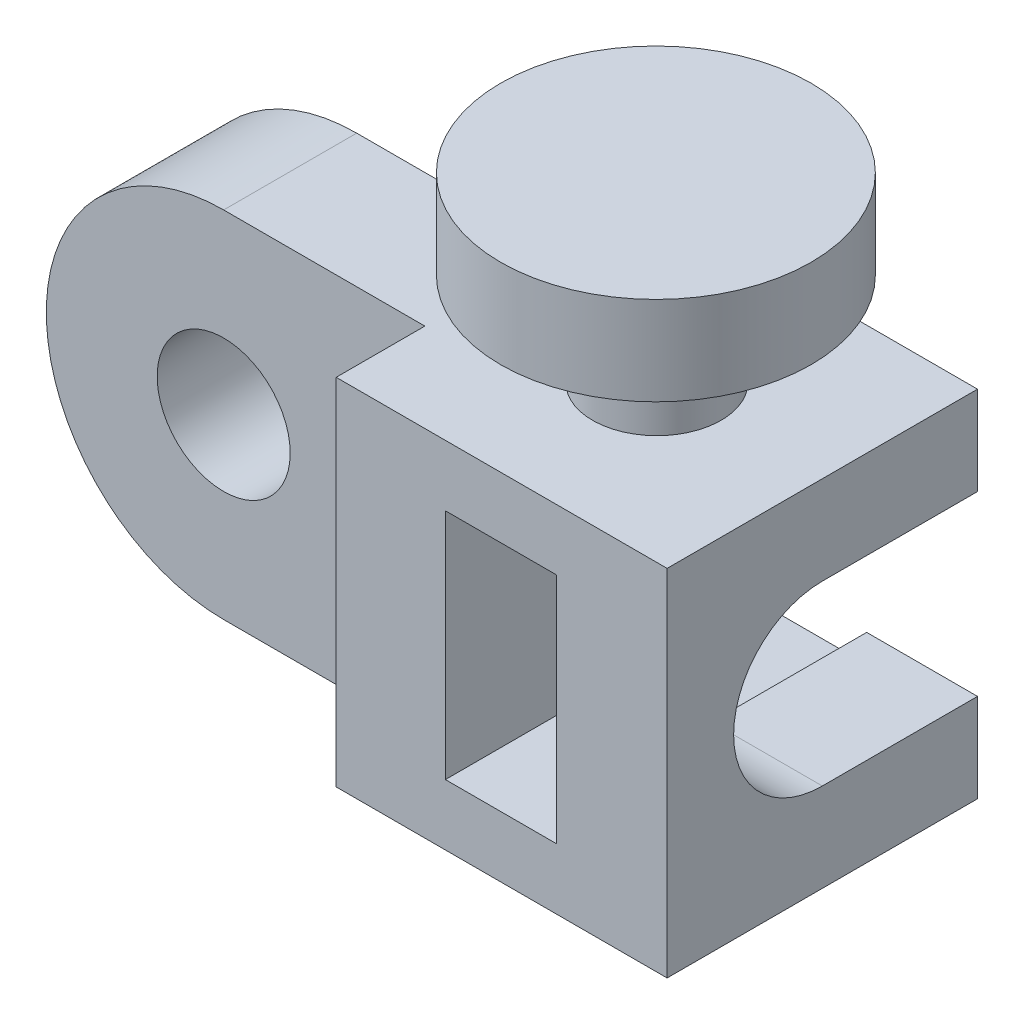
SolidWorks part; units mm, degrees
ref_plane "Спереди" through (0, 0, 0) normal (0, 0, 1) x (1, 0, 0)
ref_plane "Сверху" through (0, 0, 0) normal (0, 1, 0) x (1, 0, 0)
ref_plane "Справа" through (0, 0, 0) normal (1, 0, 0) x (0, 0, -1)
sketch "Sketch1" plane through (0, 0, 0) normal (0, 0, 1) x (1, 0, 0)
  line L0 (0, 0) -> (5.6788, 0) construction
  line L1 (0, 4) -> (12, 4)
  line L2 (0, -4) -> (12, -4)
  line L3 (12, 4) -> (12, -4)
  line L4 (12, -2) -> (12, 2)
  circle A0 centre (0, 0) radius 1.5
  circle A1 centre (0, 0) radius 4
  point P12 (12, 0)
  dimension "D1" = 3
  dimension "D2" = 8
  dimension "D3" = 4
  dimension "D4" = 4
  dimension "D5" = 12
  dimension "D6" = 4
extrude "Boss-Extrude1" add sketch "Sketch1" along normal mid plane 3
sketch "Sketch5" plane through (0, 0, 0) normal (0, 0, 1) x (1, 0, 0)
  line L0 (0, 4) -> (12, 4) construction
  line L1 (12, -4) -> (4.5369, -4)
  line L2 (12, -4) -> (12, 4)
  line L3 (12, 4) -> (4.5369, 4)
  line L4 (4.5369, -4) -> (4.5369, 4)
extrude "Boss-Extrude2" add sketch "Sketch5" along normal mid plane 7
sketch "Sketch2" plane through (0, 0, 1.5) normal (0, 0, 1) x (1, 0, 0)
  line L0 (12, 0) -> (8.25, 0) construction
  line L1 (12, 4) -> (12, -4) construction
  line L3 (7, 2.625) -> (9.5, 2.625)
  line L4 (7, 2.625) -> (7, -2.625)
  line L5 (7, -2.625) -> (9.5, -2.625)
  line L6 (9.5, 2.625) -> (9.5, -2.625)
  line L7 (7, 2.625) -> (9.5, -2.625) construction
  line L8 (7, -2.625) -> (9.5, 2.625) construction
  dimension "D1" = 2.5
  dimension "D2" = 5.25
  dimension "D3" = 2.5
extrude "Cut-Extrude1" cut sketch "Sketch2" against normal blind 6 and the other way blind 7
sketch "Sketch3" plane through (12, 0, 0) normal (1, 0, 0) x (0, 0, -1)
  circle A0 centre (0, 0) radius 2
  dimension "D1" = 4
extrude "Cut-Extrude2" cut sketch "Sketch3" against normal blind 3
sketch "Sketch6" plane through (0, 0, -3.5) normal (0, 0, -1) x (-1, 0, 0)
  line L0 (0, 0) -> (-12, 0) construction
  line L1 (-12, -4) -> (-12, 4) construction
  line L2 (-9.5, 2.625) -> (-9.5, -2.625) construction
  line L3 (-14.5, -2) -> (-9.5, -2)
  line L4 (-14.5, -2) -> (-14.5, 2)
  line L5 (-14.5, 2) -> (-9.5, 2)
  line L6 (-9.5, -2) -> (-9.5, 2)
  line L7 (-14.5, -2) -> (-9.5, 2) construction
  line L8 (-14.5, 2) -> (-9.5, -2) construction
  dimension "D1" = 4
extrude "Cut-Extrude3" cut sketch "Sketch6" against normal blind 3.5
sketch "Sketch7" plane through (0, 4, 0) normal (0, 1, 0) x (1, 0, 0)
  line L0 (12, 0) -> (4.4927, 0) construction
  line L1 (12, -3.5) -> (12, 3.5) construction
  line L2 (12, -1.5) -> (4.5369, -1.5) construction
  line L3 (0, -1.5) -> (4.5369, -1.5) construction
  line L4 (4.5369, -3.5) -> (4.5369, -1.5) construction
  line L5 (8.2685, -1.5) -> (8.2685, 1.5) construction
  circle A1 centre (8.2685, 0) radius 1.45
  dimension "D1" = 2.9
extrude "Boss-Extrude3" add sketch "Sketch7" along normal blind 2.1
sketch "Sketch8" plane through (0, 6.1, 0) normal (0, 1, 0) x (1, 0, 0)
  circle A0 centre (8.2464, 0) radius 3.5
extrude "Boss-Extrude4" add sketch "Sketch8" along normal blind 2
